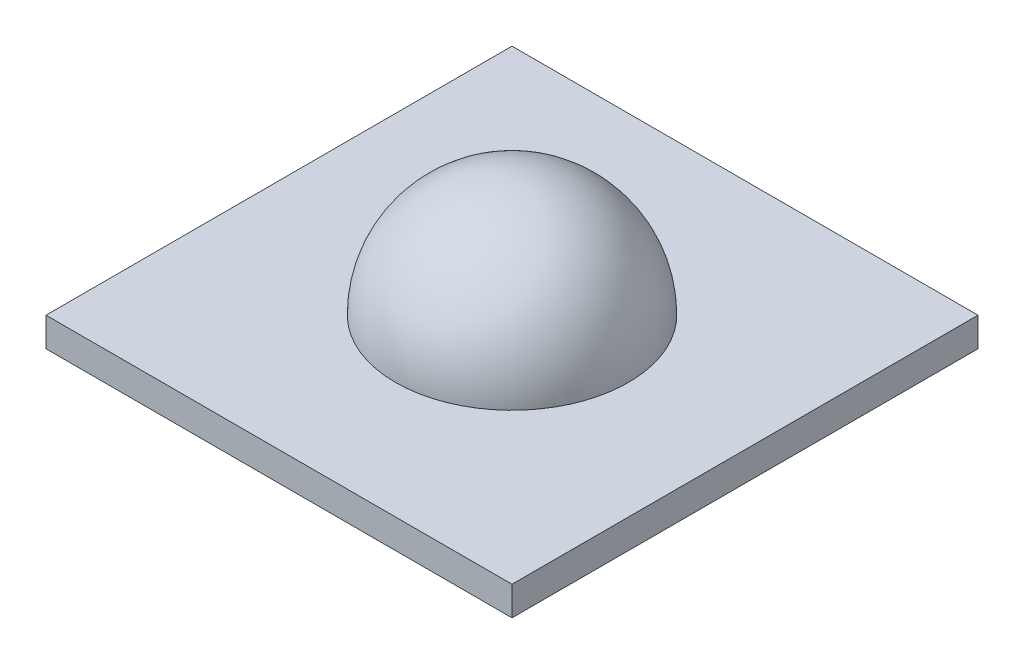
SolidWorks part; units mm, degrees
material "Pin"
ref_plane "Plan de face" through (0, 0, 0) normal (0, 0, 1) x (1, 0, 0)
ref_plane "Plan de dessus" through (0, 0, 0) normal (0, 1, 0) x (1, 0, 0)
ref_plane "Plan de droite" through (0, 0, 0) normal (1, 0, 0) x (0, 0, -1)
sketch "Esquisse1" plane through (0, 0, 0) normal (0, 1, 0) x (1, 0, 0)
  line L0 (-40, 40) -> (40, -40) construction
  line L1 (-40, 40) -> (40, 40)
  line L2 (-40, 40) -> (-40, -40)
  line L3 (-40, -40) -> (40, -40)
  line L4 (40, 40) -> (40, -40)
  line L5 (40, 40) -> (-40, -40) construction
  dimension "D1" = 80
extrude "Boss.-Extru.1" add sketch "Esquisse1" along normal blind 5
sketch "Esquisse2" plane through (0, 0, 0) normal (1, 0, 0) x (0, 0, -1)
  line L0 (0, 5) -> (0, 34.1486) construction
  line L1 (-40, 5) -> (40, 5) construction
  line L2 (-20, 5) -> (0, 5)
  line L3 (0, 5) -> (0, 25)
  arc A0 (0, 25) -> (-20, 5) centre (0, 5) ccw
  dimension "D1" = 20
revolve "Révolution2" add sketch "Esquisse2" angle 360 about L0
